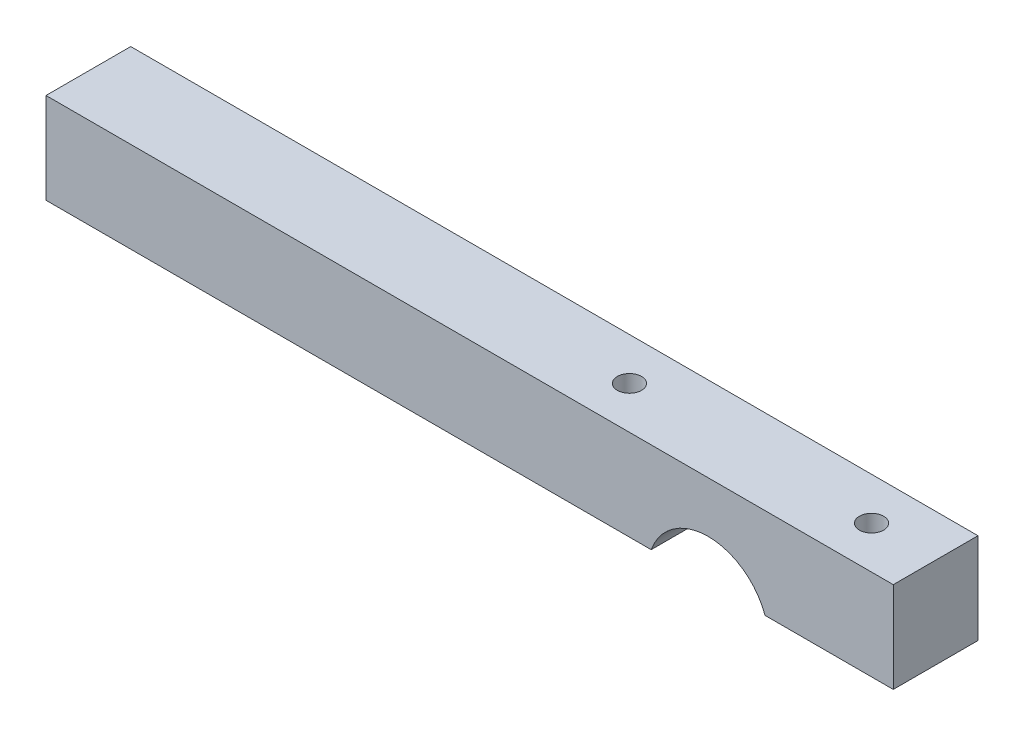
SolidWorks part; units mm, degrees
ref_plane "Front Plane" through (0, 0, 0) normal (0, 0, 1) x (1, 0, 0)
ref_plane "Top Plane" through (0, 0, 0) normal (0, 1, 0) x (1, 0, 0)
ref_plane "Right Plane" through (0, 0, 0) normal (1, 0, 0) x (0, 0, -1)
sketch "Sketch2" plane through (0, 0, 0) normal (0, 0, 1) x (1, 0, 0)
  line L0 (9.4066, 3.3934) -> (30.5934, 3.3934)
  line L1 (-109.4066, 18.3934) -> (30.5934, 18.3934)
  line L2 (-109.4066, 18.3934) -> (-109.4066, 3.3934)
  line L3 (-109.4066, 3.3934) -> (-9.4066, 3.3934)
  line L4 (30.5934, 18.3934) -> (30.5934, 3.3934)
  line L5 (77, 0) -> (-77, 0) construction
  arc A0 (-9.4066, 3.3934) -> (9.4066, 3.3934) centre (0, 0) cw
  point P7 (0, 0)
  point P8 (0, 0)
  dimension "D3" = 10
  dimension "D1" = 140
  dimension "D2" = 15
  dimension "D4" = 100
  dimension "D5" = 21.1867
extrude "Boss-Extrude1" add sketch "Sketch2" along normal blind 14
sketch "Sketch4" plane through (0, 18.3934, 0) normal (0, 1, 0) x (1, 0, 0)
  line L0 (-20, 0) -> (20, 0) construction
  line L1 (-109.4066, 0) -> (30.5934, 0) construction
  line L2 (-20, 0) -> (-20, -14) construction
  line L3 (30.5934, -14) -> (-109.4066, -14) construction
  line L4 (20, 0) -> (20, -14) construction
  circle A0 centre (20, -7) radius 2
  circle A1 centre (-20, -7) radius 2
  point P6 (0, 0)
  dimension "D2" = 4
  dimension "D3" = 4
  dimension "D1" = 40
extrude "Cut-Extrude1" cut sketch "Sketch4" against normal up to next
